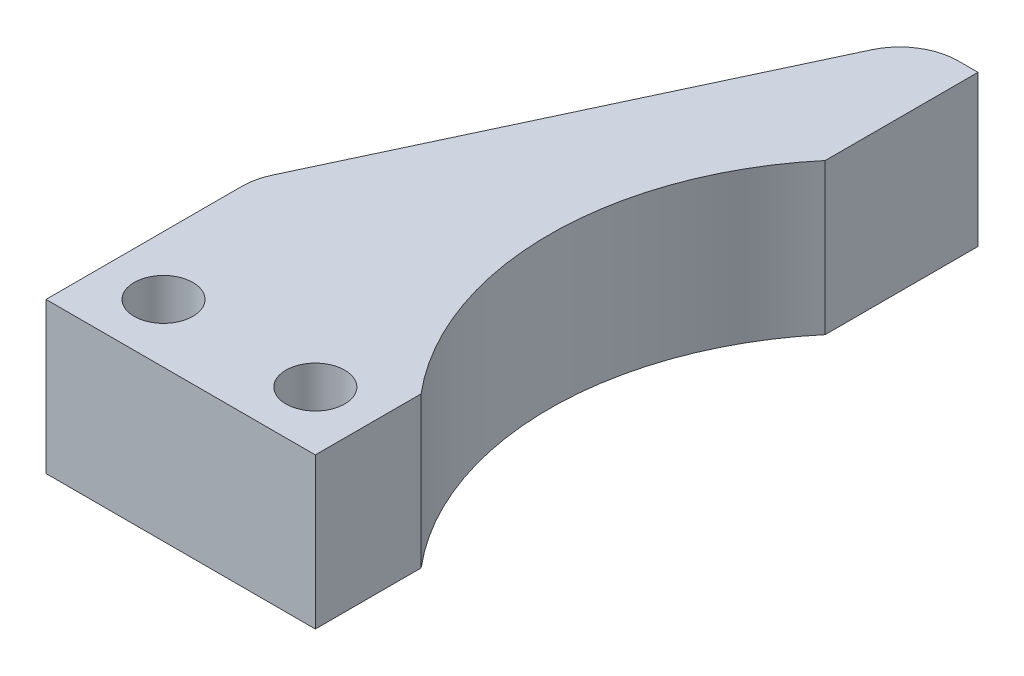
SolidWorks part; units mm, degrees
ref_plane "Front Plane" through (0, 0, 0) normal (0, 0, 1) x (1, 0, 0)
ref_plane "Top Plane" through (0, 0, 0) normal (0, 1, 0) x (1, 0, 0)
ref_plane "Right Plane" through (0, 0, 0) normal (1, 0, 0) x (0, 0, -1)
sketch "Sketch1" plane through (0, 0, 0) normal (0, 1, 0) x (1, 0, 0)
  line L0 (-13.75, -5.4) -> (0, -5.4)
  line L1 (-13.75, -5.4) -> (-13.75, 4.6)
  line L2 (-13.4671, 5.8717) -> (-3.7171, 26.7029)
  line L3 (-1, 28.4312) -> (0, 28.4312)
  line L4 (0, 28.4312) -> (0, 20.6312)
  line L5 (0, -5.4) -> (0, 0)
  line L6 (-6.875, -18.3439) -> (-6.875, 41.8929) construction
  line L7 (0, 28.4312) -> (3.85, 28.4312)
  line L8 (3.85, 28.4312) -> (3.85, 20.6312)
  line L9 (3.85, 20.6312) -> (0, 20.6312)
  arc A0 (0, 0) -> (0, 20.6312) centre (12.2306, 10.3156) cw
  arc A1 (-3.7171, 26.7029) -> (-1, 28.4312) centre (-1, 25.4312) cw
  arc A2 (-13.75, 4.6) -> (-13.4671, 5.8717) centre (-10.75, 4.6) cw
  circle A3 centre (-10.75, -2.4) radius 1.5
  circle A5 centre (-3, -2.4) radius 1.5
  dimension "D1" = 3
  dimension "D2" = 3
  dimension "D6" = 16
  dimension "D10" = 3
  dimension "D12" = 3
  dimension "D3" = 13.75
  dimension "D4" = 5.4
  dimension "D5" = 10
  dimension "D7" = 23
  dimension "D8" = 7.8
  dimension "D9" = 1
  dimension "D11" = 3
  dimension "D13" = 3.85
extrude "Boss-Extrude3" add sketch "Sketch1" along normal mid plane 7.7 contours L6 L0 L5 A0 L4 L3 A1 L2 A5 | L0 L6 L2 A2 L1 A3
